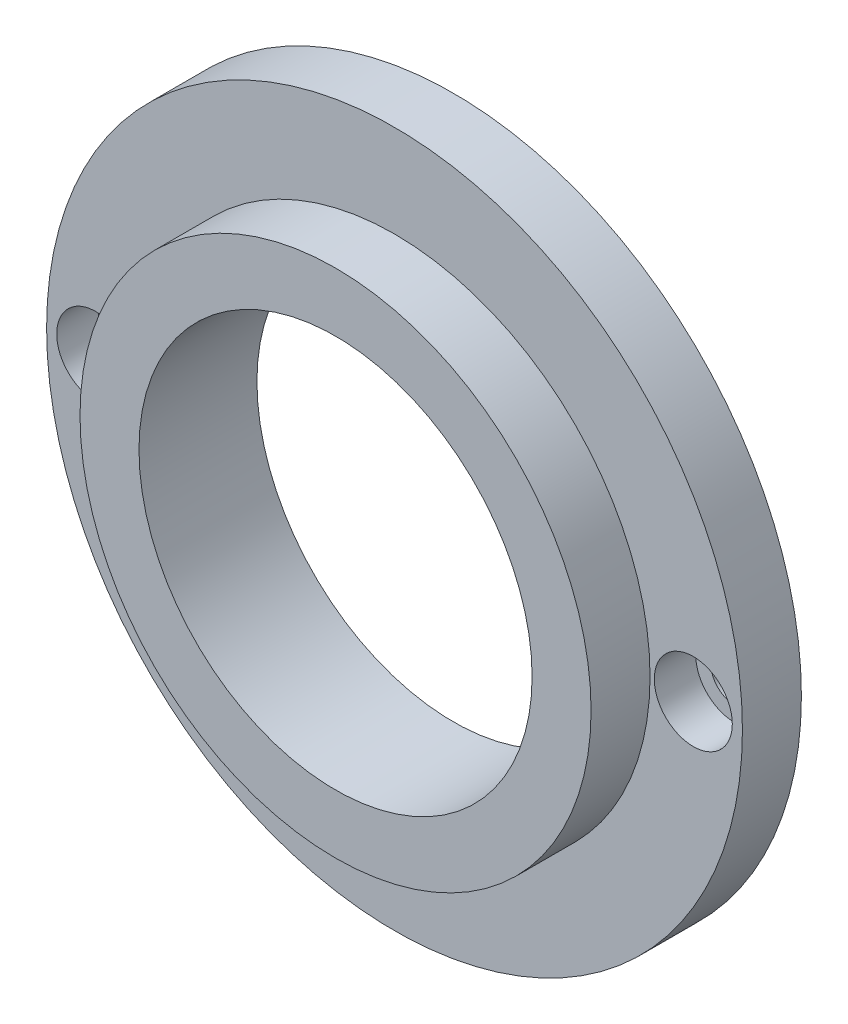
SolidWorks part; units mm, degrees
ref_plane "Plan de face" through (0, 0, 0) normal (0, 0, 1) x (1, 0, 0)
ref_plane "Plan de dessus" through (0, 0, 0) normal (0, 1, 0) x (1, 0, 0)
ref_plane "Plan de droite" through (0, 0, 0) normal (1, 0, 0) x (0, 0, -1)
sketch "Esquisse1" [suppressed] plane through (0, 0, 0) normal (0, 0, 1) x (1, 0, 0)
  circle A0 centre (0, 0) radius 40.8746
sketch "Esquisse10" plane through (0, 0, 0) normal (0, 0, 1) x (1, 0, 0)
  circle A0 centre (0, 0) radius 13
  circle A1 centre (0, 0) radius 10
extrude "Boss.-Extru.2" add sketch "Esquisse10" along normal blind 3
sketch "Esquisse11" plane through (0, 0, 0) normal (0, 0, -1) x (-1, 0, 0)
  circle A0 centre (0, 0) radius 10
  circle A1 centre (0, 0) radius 17.7
extrude "Boss.-Extru.3" add sketch "Esquisse11" along normal blind 3
sketch "Sketch1" plane through (0, 0, 0) normal (0, 0, 1) x (1, 0, 0)
  line L0 (-15.2, 0) -> (-17.7, 0)
  line L1 (15.2, 0) -> (17.7, 0)
  circle A2 centre (0, 0) radius 17.7 construction
  point P11 (0, 0)
  point P12 (0, 0)
  point P13 (0, 0)
  point P14 (0, 0)
  point P15 (0, 0)
hole_wizard "CBORE for #2 Fillister Head Machine Screw1" positions "Sketch2" profile "Sketch3" counterbore size "#2" standard "ANSI Inch" end condition through all
sketch "Sketch2" plane through (0, 0, 0) normal (0, 0, 1) x (1, 0, 0)
  point P0 (-15.2, 0)
  point P3 (15.2, 0)
sketch "Sketch3" plane through (-15.2, 0, 0) normal (1, 0, 0) x (0, -1, 0)
  line L0 (0, 0) -> (0, 3)
  line L1 (0, 3) -> (1.2192, 3)
  line L3 (1.2192, 3) -> (1.2192, 2.1082)
  line L4 (1.2192, 2.1082) -> (1.985, 2.1082)
  line L5 (1.985, 2.1082) -> (1.985, 0)
  line L7 (1.985, 0) -> (0, 0)
  line L11 (0, -6.35) -> (0, 107.95) construction
  dimension "Thru Hole Dia." = 2.4384
  dimension "Thru Hole Depth" = 3
  dimension "C'Bore Dia." = 3.97
  dimension "C'Bore Depth" = 2.1082
